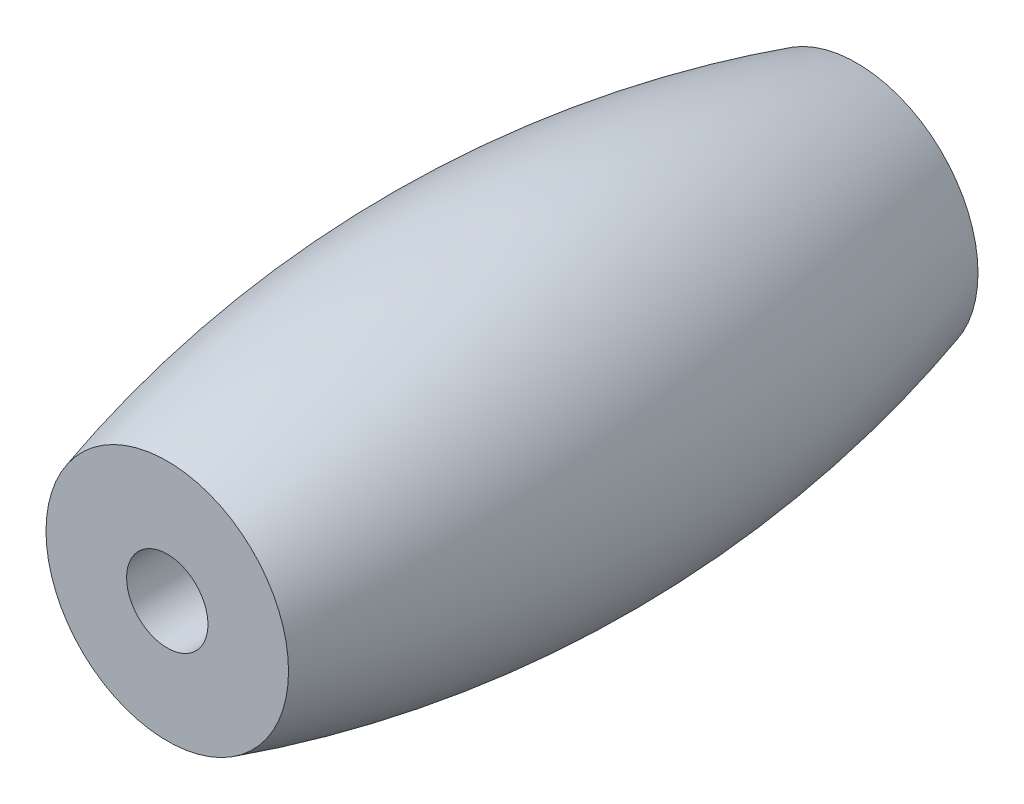
SolidWorks part; units mm, degrees
ref_plane "Front Plane" through (0, 0, 0) normal (0, 0, 1) x (1, 0, 0)
ref_plane "Top Plane" through (0, 0, 0) normal (0, 1, 0) x (1, 0, 0)
ref_plane "Right Plane" through (0, 0, 0) normal (1, 0, 0) x (0, 0, -1)
sketch "Sketch1" plane through (0, 0, 0) normal (1, 0, 0) x (0, 0, -1)
  line L0 (0, 0) -> (0, 31.83) construction
  line L1 (12.2305, 16.8762) -> (20.7305, 2.1538) construction
  line L2 (-8.5, 20.1859) -> (8.5, 20.1859) construction
  line L3 (-8.5, 20.1859) -> (-8.5, 30.6741) construction
  line L4 (-8.5, 30.6741) -> (8.5, 30.6741) construction
  line L5 (8.5, 20.1859) -> (8.5, 30.6741) construction
  line L6 (-8.5, 20.1859) -> (8.5, 30.6741) construction
  line L7 (-8.5, 30.6741) -> (8.5, 20.1859) construction
  line L8 (-8.5, 19.03) -> (8.5, 19.03) construction
  line L9 (-8.5, 19.03) -> (-8.5, 31.83) construction
  line L10 (-8.5, 31.83) -> (8.5, 31.83) construction
  line L11 (8.5, 19.03) -> (8.5, 31.83) construction
  line L12 (-8.5, 19.03) -> (8.5, 31.83) construction
  line L13 (-8.5, 31.83) -> (8.5, 19.03) construction
  line L14 (23.3156, 23.2762) -> (31.8156, 8.5538) construction
  line L15 (20.7305, 2.1538) -> (31.8156, 8.5538) construction
  line L16 (12.2305, 16.8762) -> (23.3156, 23.2762) construction
  line L17 (20.7305, -2.1538) -> (12.2305, -16.8762) construction
  line L18 (31.8156, -8.5538) -> (23.3156, -23.2762) construction
  line L19 (12.2305, -16.8762) -> (23.3156, -23.2762) construction
  line L20 (20.7305, -2.1538) -> (31.8156, -8.5538) construction
  line L21 (8.5, -19.03) -> (-8.5, -19.03) construction
  line L22 (8.5, -31.83) -> (-8.5, -31.83) construction
  line L23 (-8.5, -19.03) -> (-8.5, -31.83) construction
  line L24 (8.5, -19.03) -> (8.5, -31.83) construction
  line L25 (-12.2305, -16.8762) -> (-20.7305, -2.1538) construction
  line L26 (-23.3156, -23.2762) -> (-31.8156, -8.5538) construction
  line L27 (-20.7305, -2.1538) -> (-31.8156, -8.5538) construction
  line L28 (-12.2305, -16.8762) -> (-23.3156, -23.2762) construction
  line L29 (-20.7305, 2.1538) -> (-12.2305, 16.8762) construction
  line L30 (-31.8156, 8.5538) -> (-23.3156, 23.2762) construction
  line L31 (-12.2305, 16.8762) -> (-23.3156, 23.2762) construction
  line L32 (-20.7305, 2.1538) -> (-31.8156, 8.5538) construction
  line L36 (-8.5, 28.6741) -> (8.5, 28.6741) construction
  line L37 (-8.5, 28.6741) -> (-8.5, 30.6741) construction
  line L38 (8.5, 30.6741) -> (8.5, 28.6741) construction
  line L39 (0, 25.43) -> (11.8986, 25.43) construction
  line L40 (-8.5, 25.43) -> (8.9, 25.43)
  line L41 (8.9, 25.43) -> (8.9, 28.5604)
  line L42 (-8.5, 25.43) -> (-8.9, 25.43)
  line L43 (-8.9, 25.43) -> (-8.9, 28.5604)
  circle A0 centre (0, 0) radius 31.83 construction
  arc A1 (-8.5, 30.6741) -> (8.5, 30.6741) centre (0, 0) cw construction
  arc A2 (-8.5, 28.6741) -> (8.5, 28.6741) centre (0, -2) cw
  arc A3 (-8.9, 28.5604) -> (-8.5, 28.6741) centre (0, -2) cw
  arc A4 (8.5, 28.6741) -> (8.9, 28.5604) centre (0, -2) cw
  point P3 (0, 25.43)
  point P9 (0, 25.43)
  point P36 (0, 0)
  dimension "D1" = 63.66
  dimension "D2" = 17
  dimension "D3" = 12.8
  dimension "D5" = 2
  dimension "D6" = 8.8
  dimension "D7" = 6.4882
  dimension "D8" = 0.4
  dimension "D9" = 17.8
  dimension "D4" = 6
revolve "Revolve1" add sketch "Sketch1" angle 360 about L39
sketch "Sketch2" plane through (0, 0, -8.9) normal (0, 0, -1) x (-1, 0, 0)
  circle A0 centre (0, 25.43) radius 1.05
  dimension "D1" = 2.1
extrude "Cut-Extrude1" cut sketch "Sketch2" against normal through all
